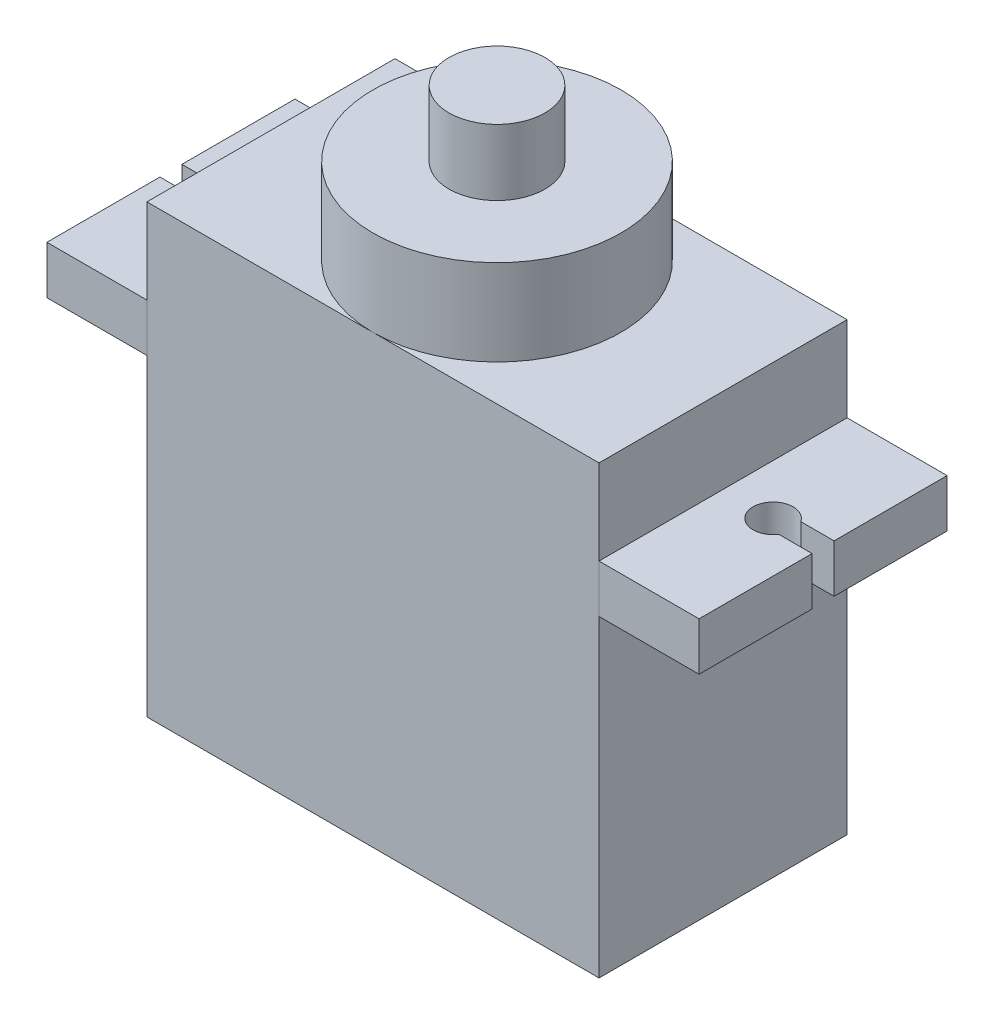
SolidWorks part; units mm, degrees
ref_plane "前视基准面" through (0, 0, 0) normal (0, 0, 1) x (1, 0, 0)
ref_plane "上视基准面" through (0, 0, 0) normal (0, 1, 0) x (1, 0, 0)
ref_plane "右视基准面" through (0, 0, 0) normal (1, 0, 0) x (0, 0, -1)
sketch "草图1" plane through (0, 0, 0) normal (0, 1, 0) x (1, 0, 0)
  line L1 (-11.3, 6.2) -> (11.3, 6.2)
  line L2 (-11.3, 6.2) -> (-11.3, -6.2)
  line L3 (-11.3, -6.2) -> (11.3, -6.2)
  line L4 (11.3, 6.2) -> (11.3, -6.2)
  line L5 (0, -6.2) -> (0, 6.2) construction
  line L6 (-11.3, 0) -> (11.3, 0) construction
  point P0 (0, 0)
  dimension "D1" = 22.6
  dimension "D2" = 12.4
extrude "凸台-拉伸1" add sketch "草图1" along normal blind 22.3
sketch "草图2" plane through (0, 0, 6.2) normal (0, 0, 1) x (1, 0, 0)
  line L0 (11.3, 22.3) -> (11.3, 0) construction
  line L1 (11.3, 18.05) -> (16.3, 18.05)
  line L2 (11.3, 18.05) -> (11.3, 15.65)
  line L3 (11.3, 15.65) -> (16.3, 15.65)
  line L4 (16.3, 18.05) -> (16.3, 15.65)
  line L5 (-11.3, 22.3) -> (11.3, 22.3) construction
  line L6 (0, 0) -> (0, 13.1092) construction
  line L7 (-11.3, 15.65) -> (-16.3, 15.65)
  line L8 (-16.3, 18.05) -> (-16.3, 15.65)
  line L9 (-11.3, 18.05) -> (-16.3, 18.05)
  line L10 (-11.3, 18.05) -> (-11.3, 15.65)
  dimension "D1" = 4.25
  dimension "D2" = 2.4
  dimension "D3" = 5
extrude "凸台-拉伸2" add sketch "草图2" against normal through all separate body
sketch "草图3" plane through (0, 18.05, 0) normal (0, 1, 0) x (1, 0, 0)
  line L0 (14.6352, 0.55) -> (16.3, 0.55)
  line L1 (16.3, 6.2) -> (16.3, -6.2) construction
  line L2 (16.3, 0.55) -> (16.3, -0.55)
  line L3 (16.3, -0.55) -> (14.6352, -0.55)
  line L4 (0, 0) -> (13.8, 0) construction
  line L5 (0, 0) -> (0, 7.8737) construction
  line L12 (-14.6352, -0.55) -> (-16.3, -0.55)
  line L13 (-16.3, 0.55) -> (-14.6352, 0.55)
  line L19 (-16.3, 0.55) -> (-16.3, -0.55)
  arc A0 (14.6352, 0.55) -> (14.6352, -0.55) centre (13.8, 0) ccw
  arc A1 (-14.6352, 0.55) -> (-14.6352, -0.55) centre (-13.8, 0) cw
  dimension "D1" = 2
  dimension "D2" = 2.5
  dimension "D3" = 1.1
extrude "切除-拉伸1" cut sketch "草图3" against normal through all
sketch "草图4" plane through (0, 22.3, 0) normal (0, 1, 0) x (1, 0, 0)
  circle A0 centre (0, 0) radius 6.2
  dimension "D1" = 12.4
extrude "凸台-拉伸3" add sketch "草图4" along normal blind 4.3
sketch "草图5" plane through (0, 26.6, 0) normal (0, 1, 0) x (1, 0, 0)
  circle A0 centre (0, 0) radius 2.4
  dimension "D1" = 4.8
extrude "凸台-拉伸4" add sketch "草图5" along normal blind 3.3
sketch "草图6" plane through (-11.3, 0, 0) normal (-1, 0, 0) x (0, 0, 1)
  line L0 (-6.2, 0) -> (6.2, 0) construction
  circle A0 centre (0, 4.5) radius 0.6
  circle A1 centre (1.2, 4.5) radius 0.6
  circle A2 centre (-1.2, 4.5) radius 0.6
  line M2 (6.2, 0) -> (6.2, 22.3)
  dimension "D1" = 1.2
  dimension "D2" = 4.5
extrude "凸台-拉伸8" add sketch "草图6" along normal blind 2.3 separate body contours A2 | A0 M2 | A1
